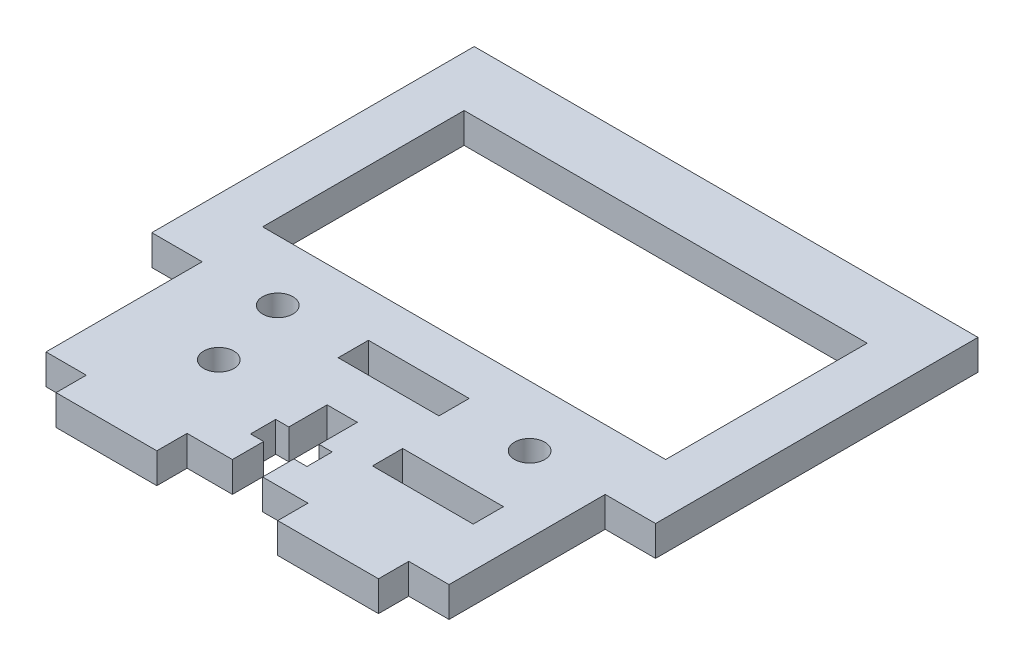
SolidWorks part; units mm, degrees
ref_plane "Front Plane" through (0, 0, 0) normal (0, 0, 1) x (1, 0, 0)
ref_plane "Top Plane" through (0, 0, 0) normal (0, 1, 0) x (1, 0, 0)
ref_plane "Right Plane" through (0, 0, 0) normal (1, 0, 0) x (0, 0, -1)
sketch "Sketch2" plane through (0, 0, 0) normal (0, 1, 0) x (1, 0, 0)
  line L0 (0, 15.5) -> (5, 15.5)
  line L1 (0, 0) -> (-4, 0)
  line L2 (0, 0) -> (0, 15.5)
  line L4 (-40, 0) -> (-40, 15.5)
  line L5 (5, 15.5) -> (5, 47.5)
  line L6 (0, 41.5) -> (-40, 41.5)
  line L7 (-45, 47.5) -> (-45, 15.5)
  line L8 (-45, 15.5) -> (-40, 15.5)
  line L9 (-20, 41.5) -> (-20, 9.4) construction
  line L11 (0, 21.5) -> (-40, 21.5)
  line L12 (-40, 21.5) -> (-40, 41.5)
  line L13 (-40, 41.5) -> (0, 41.5)
  line L14 (0, 41.5) -> (0, 21.5)
  line L15 (5, 47.5) -> (-45, 47.5)
  line L16 (-4, 0) -> (-4, -3)
  line L17 (-4, -3) -> (-14, -3)
  line L18 (-14, -3) -> (-14, 0)
  line L19 (-14, 0) -> (-18.5, 0)
  line L20 (-26, -3) -> (-26, 0)
  line L21 (-36, -3) -> (-26, -3)
  line L22 (-36, 0) -> (-36, -3)
  line L23 (-36, 0) -> (-40, 0)
  line L25 (-18.5, 0) -> (-18.5, 3.1)
  line L26 (-18.5, 3.1) -> (-17.2, 3.1)
  line L27 (-17.2, 3.1) -> (-17.2, 5.6)
  line L28 (-17.2, 5.6) -> (-18.5, 5.6)
  line L29 (-18.5, 5.6) -> (-18.5, 9.4)
  line L30 (-18.5, 9.4) -> (-21.5, 9.4)
  line L31 (-21.5, 9.4) -> (-21.5, 5.6)
  line L32 (-21.5, 5.6) -> (-22.8, 5.6)
  line L33 (-22.8, 5.6) -> (-22.8, 3.1)
  line L34 (-22.8, 3.1) -> (-21.5, 3.1)
  line L35 (-21.5, 3.1) -> (-21.5, 0)
  line L36 (-21.5, 0) -> (-26, 0)
  line L37 (-15, 14) -> (-15, 17)
  line L38 (-15, 17) -> (-25, 17)
  line L39 (-25, 17) -> (-25, 14)
  line L40 (-25, 14) -> (-15, 14)
  line L44 (-14, 6.4) -> (-4, 6.4)
  line L45 (-4, 6.4) -> (-4, 9.4)
  line L46 (-4, 9.4) -> (-14, 9.4)
  line L47 (-14, 9.4) -> (-14, 6.4)
  circle A5 centre (-7.5, 15.5) radius 1.5
  circle A6 centre (-32.5, 15.5) radius 1.5
  circle A7 centre (-30.75, 7.9) radius 1.5
  point P14 (-15, 15.5)
  point P23 (-4, 0)
  point P51 (0, 0)
  point P52 (-14, 7.9)
  point P53 (0, 0)
  point P55 (-39.9403, -0.2415)
  dimension "D6" = 3
  dimension "D7" = 7.5
  dimension "D8" = 9.25
  dimension "D1" = 15.5
  dimension "D2" = 40
  dimension "D3" = 5
  dimension "D4" = 15
  dimension "D5" = 32
  dimension "D9" = 20
  dimension "D10" = 6
  dimension "D11" = 4
  dimension "D12" = 10
  dimension "D13" = 3
  dimension "D14" = 1.3
  dimension "D15" = 3.1
  dimension "D16" = 2.5
  dimension "D17" = 3.8
  dimension "D18" = 3
  dimension "D19" = 4.5
extrude "Boss-Extrude1" add sketch "Sketch2" along normal blind 3
